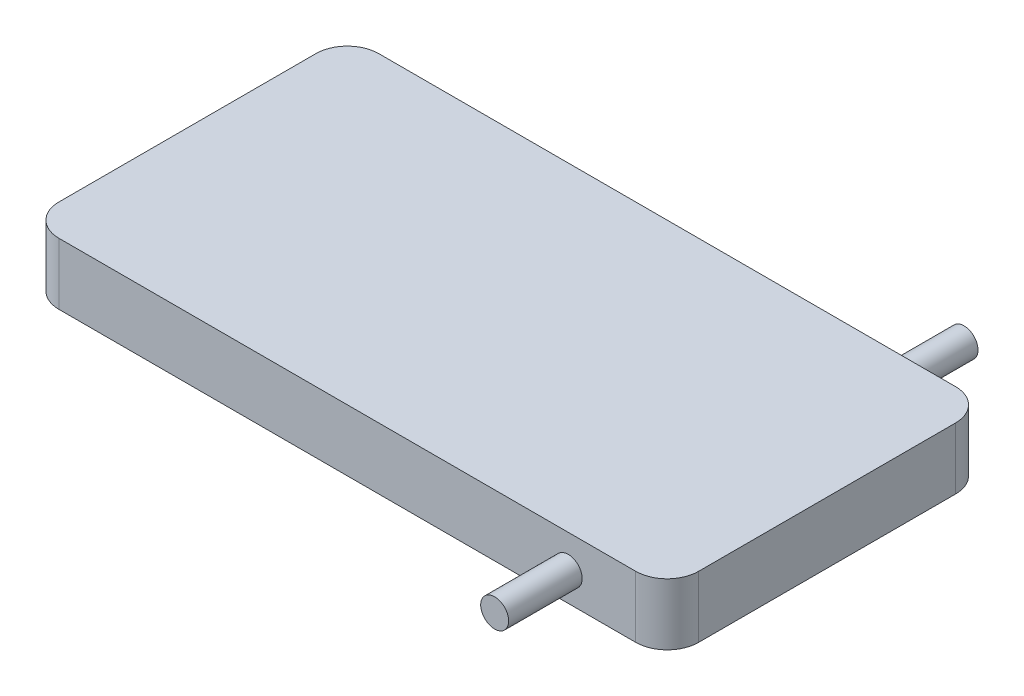
SolidWorks part; units mm, degrees
ref_plane "Front Plane" through (0, 0, 0) normal (0, 0, 1) x (1, 0, 0)
ref_plane "Top Plane" through (0, 0, 0) normal (0, 1, 0) x (1, 0, 0)
ref_plane "Right Plane" through (0, 0, 0) normal (1, 0, 0) x (0, 0, -1)
sketch "Sketch2" plane through (-97.4825, 0, 34.7351) normal (0, 1, 0) x (1, 0, 0)
  line L1 (-121.146, 85.1479) -> (82.054, 85.1479)
  line L2 (-121.146, 85.1479) -> (-121.146, -16.4521)
  line L3 (-121.146, -16.4521) -> (82.054, -16.4521)
  line L4 (82.054, 85.1479) -> (82.054, -16.4521)
  dimension "D1" = 203.2
  dimension "D2" = 101.6
extrude "Boss-Extrude1" add sketch "Sketch2" along normal blind 19.558 contours L2 L1 L4 L3
sketch3d "3DSketch1" plane through (0, 0, 0) normal (0, 0, 1) x (1, 0, 0)
fillet "Fillet1" radius 10 1 edges at (-15.4285, 9.779, 51.1873)
fillet "Fillet2" radius 10 1 edges at (-218.6285, 9.779, -50.4127)
fillet "Fillet3" radius 10 1 edges at (-218.6285, 9.779, 51.1873)
fillet "Fillet4" radius 10 1 edges at (-15.4285, 9.779, -50.4127)
sketch "Sketch3" plane through (0, 0, -50.4127) normal (0, 0, -1) x (-1, 0, 0)
  circle A0 centre (46.8713, 9.0495) radius 4.445
  dimension "D1" = 8.89
extrude "Boss-Extrude3" add sketch "Sketch3" along normal blind 24.13
mirror "Mirror2" about plane through (0, 0, 0) normal (0, 0, 1) of "Boss-Extrude3"
sketch "Sketch4" plane through (0, 0, 0) normal (0, -1, 0) x (1, 0, 0)
  line L0 (-240.9281, 1.4591) -> (19.0302, 1.4591) construction
  line L1 (-117.6364, 73.1969) -> (-117.6364, -66.1447) construction
  line L2 (-175.513, 73.1969) -> (-175.513, -68.8196) construction
  circle A0 centre (-175.513, 2.1886) radius 19.05
  dimension "D1" = 38.1
extrude "Cut-Extrude1" cut sketch "Sketch4" against normal blind 2.54
